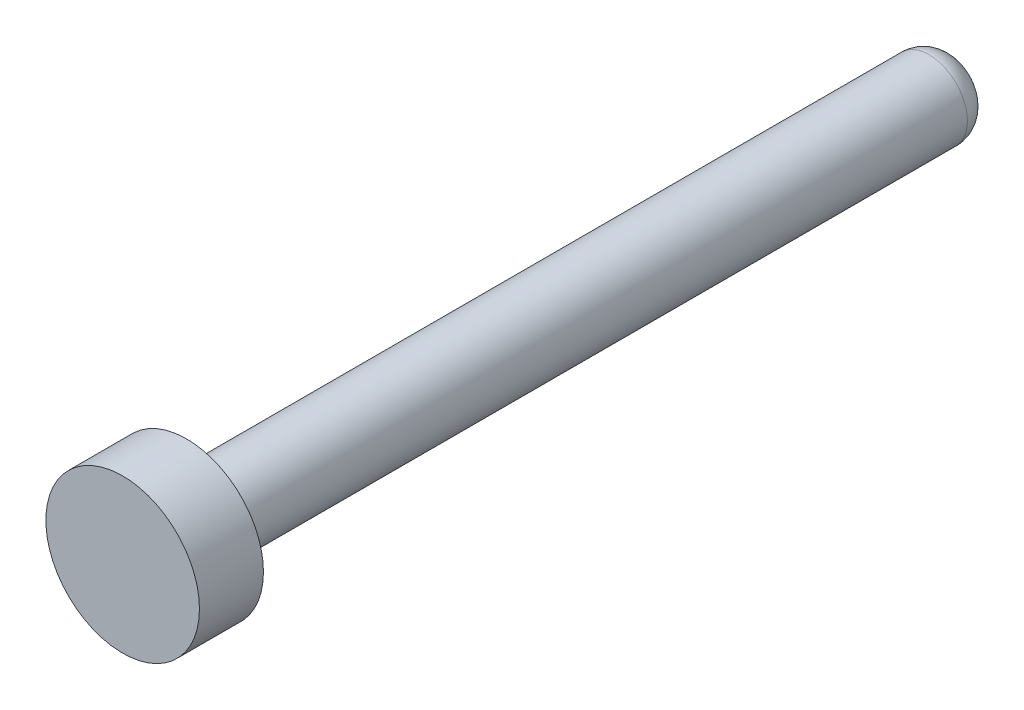
SolidWorks part; units mm, degrees
ref_plane "Front" through (0, 0, 0) normal (0, 0, 1) x (1, 0, 0)
ref_plane "Top" through (0, 0, 0) normal (0, 1, 0) x (1, 0, 0)
ref_plane "Right" through (0, 0, 0) normal (1, 0, 0) x (0, 0, -1)
sketch "Sketch1" plane through (0, 0, 0) normal (0, 0, 1) x (1, 0, 0)
  circle A0 centre (0, 0) radius 3
  dimension "D1" = 6
extrude "Boss-Extrude1" add sketch "Sketch1" along normal blind 65
sketch "Sketch2" plane through (0, 0, 65) normal (0, 0, 1) x (1, 0, 0)
  circle A0 centre (0, 0) radius 6
  dimension "D1" = 12
extrude "Boss-Extrude2" add sketch "Sketch2" against normal blind 5
fillet "Fillet1" radius 2 1 edges at (3, 0, 0)
